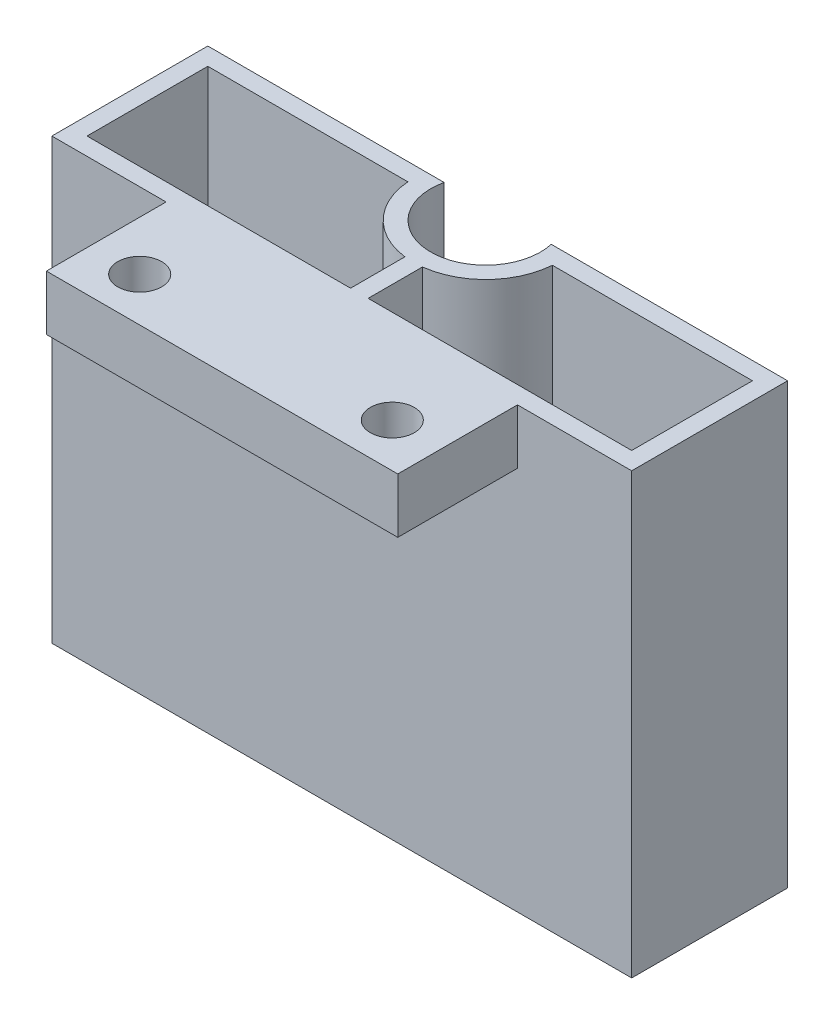
SolidWorks part; units mm, degrees
ref_plane "Plano frontal" through (0, 0, 0) normal (0, 0, 1) x (1, 0, 0)
ref_plane "Plano superior" through (0, 0, 0) normal (0, 1, 0) x (1, 0, 0)
ref_plane "Plano direito" through (0, 0, 0) normal (1, 0, 0) x (0, 0, -1)
sketch "Esboço2" plane through (0, 0, 0) normal (0, 1, 0) x (1, 0, 0)
  line L0 (-5.75, -1) -> (5.75, -1) construction
  line L1 (-8, 3) -> (8, 3)
  line L2 (-8, 3) -> (-8, -3)
  line L3 (-8, -3) -> (8, -3)
  line L4 (8, 3) -> (8, -3)
  line L5 (-8, 3) -> (8, -3) construction
  line L6 (-8, -3) -> (8, 3) construction
  circle A0 centre (-5.75, -1) radius 1
  circle A1 centre (5.75, -1) radius 1
  point P0 (0, 0)
  point P10 (0, -1)
  dimension "D3" = 2
  dimension "D4" = 2
  dimension "D1" = 16
  dimension "D2" = 6
  dimension "D5" = 11.5
  dimension "D6" = 2
extrude "Ressalto-extrusão4" add sketch "Esboço2" along normal blind 2.5
sketch "Esboço4" plane through (0, 2.5, 0) normal (0, 1, 0) x (1, 0, 0)
  line L0 (13.2, 2.45) -> (-13.2, 2.45)
  line L1 (-13.2, 9.55) -> (-2.4387, 9.55)
  line L2 (-13.2, 9.55) -> (-13.2, 2.45)
  line L3 (2.4387, 9.55) -> (13.2, 9.55)
  line L4 (13.2, 9.55) -> (13.2, 2.45)
  line L5 (3.2905, 8.75) -> (12.4, 8.75)
  line L9 (-0.4, 3.25) -> (-12.4, 3.25)
  line L10 (-12.4, 8.75) -> (-3.2905, 8.75)
  line L11 (-12.4, 8.75) -> (-12.4, 3.25)
  line L12 (0.4, 3.25) -> (12.4, 3.25)
  line L13 (12.4, 8.75) -> (12.4, 3.25)
  line L14 (-0.4, -3.85) -> (0.4, -3.85)
  line L17 (-0.4, 3.25) -> (-0.4, 5.7243)
  line L18 (0, 0) -> (0, 2.45) construction
  line L19 (0.4, 3.25) -> (0.4, 5.7243)
  arc A0 (-2.4387, 9.55) -> (2.4387, 9.55) centre (0, 9) ccw
  arc A1 (-3.2905, 8.75) -> (-0.4, 5.7243) centre (0, 9) ccw
  circle A2 centre (0, 9) radius 3.3 construction
  circle A3 centre (0, 9) radius 2.5 construction
  arc A4 (0.4, 5.7243) -> (3.2905, 8.75) centre (0, 9) ccw
  circle A5 centre (-5.75, -1) radius 1 construction
  point P1 (-12.4, 6)
  point P8 (0, 2.45)
  dimension "D9" = 5
  dimension "D1" = 0.8
  dimension "D2" = 26.4
  dimension "D3" = 5.5
  dimension "D4" = 3
  dimension "D5" = 0.8
  dimension "D6" = 0.8
  dimension "D7" = 0.8
  dimension "D8" = 7
  dimension "D11" = 0.8
  dimension "D10" = 0.8
extrude "Ressalto-extrusão6" add sketch "Esboço4" against normal blind 20
sketch "Sketch2" plane through (0, 2.5, 0) normal (0, 1, 0) x (1, 0, 0)
  line L0 (2.4387, 9.55) -> (13.2, 9.55)
  line L1 (-8, 2.45) -> (8, 2.45)
  line L2 (-8, 2.45) -> (-8, -3)
  line L3 (-8, -3) -> (8, -3)
  line L4 (8, 2.45) -> (8, -3)
  line L5 (-13.2, 9.55) -> (-2.4387, 9.55)
  line L6 (-13.2, 9.55) -> (-13.2, 2.45)
  line L7 (-13.2, 2.45) -> (13.2, 2.45)
  line L8 (13.2, 9.55) -> (13.2, 2.45)
  line L9 (-12.4, 8.75) -> (-3.2905, 8.75)
  line L10 (-12.4, 8.75) -> (-12.4, 3.25)
  line L11 (-12.4, 3.25) -> (-0.4, 3.25)
  line L12 (-0.4, 5.7243) -> (-0.4, 3.25)
  line L13 (0.4, 3.25) -> (12.4, 3.25)
  line L14 (0.4, 3.25) -> (0.4, 5.7243)
  line L15 (3.2905, 8.75) -> (12.4, 8.75)
  line L16 (12.4, 3.25) -> (12.4, 8.75)
  circle A0 centre (-5.75, -1) radius 1
  circle A1 centre (5.75, -1) radius 1
  arc A2 (-2.4387, 9.55) -> (2.4387, 9.55) centre (0, 9) ccw
  arc A3 (-3.2905, 8.75) -> (-0.4, 5.7243) centre (0, 9) ccw
  arc A4 (0.4, 5.7243) -> (3.2905, 8.75) centre (0, 9) ccw
